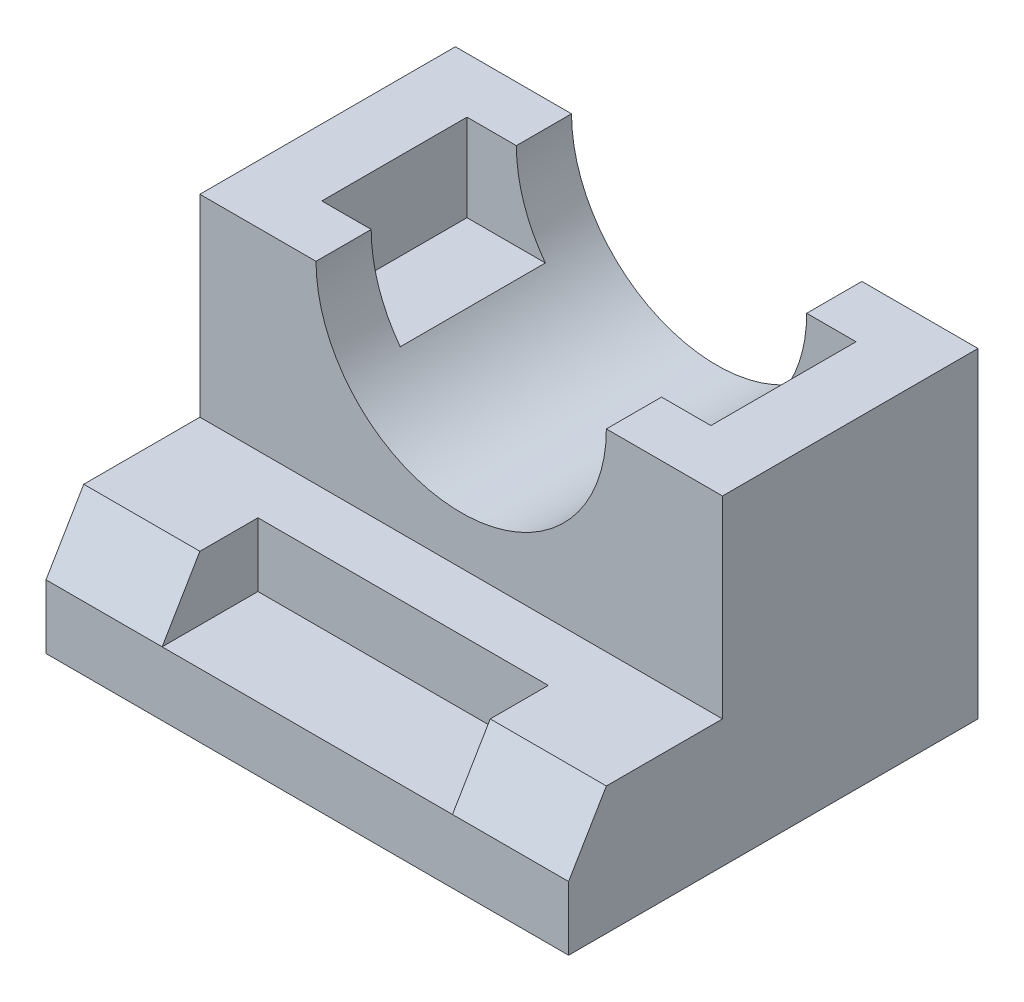
SolidWorks part; units mm, degrees
ref_plane "Front Plane" through (0, 0, 0) normal (0, 0, 1) x (1, 0, 0)
ref_plane "Top Plane" through (0, 0, 0) normal (0, 1, 0) x (1, 0, 0)
ref_plane "Right Plane" through (0, 0, 0) normal (1, 0, 0) x (0, 0, -1)
sketch "Sketch1" plane through (0, 0, 0) normal (1, 0, 0) x (0, 0, -1)
  line L0 (0, 0) -> (1117.6, 0)
  line L1 (1117.6, 0) -> (1117.6, 1403.35)
  line L2 (1117.6, 1403.35) -> (0, 1403.35)
  line L3 (0, 1403.35) -> (0, 0)
extrude "Boss-Extrude1" add sketch "Sketch1" along normal blind 2286 contours L3 L0 L1 L2
sketch "Sketch2" plane through (0, 0, 0) normal (0, 0, 1) x (1, 0, 0)
  line L0 (0, 0) -> (0, 558.8)
  line L1 (0, 1403.35) -> (0, 0) construction
  line L2 (0, 558.8) -> (2286, 558.8)
  line L3 (2286, 1403.35) -> (2286, 0) construction
  line L4 (2286, 558.8) -> (2286, 0)
  line L5 (2286, 0) -> (0, 0) construction
  line L6 (2286, 0) -> (0, 0)
  dimension "D1" = 2286
  dimension "D2" = 558.8
  dimension "D3" = 1403.35
extrude "Boss-Extrude2" add sketch "Sketch2" along normal blind 673.1 contours L6 L0 L2 L4
sketch "Sketch3" plane through (0, 0, 0) normal (-1, 0, 0) x (0, 0, 1)
  line L2 (673.1, 0) -> (673.1, 558.8) construction
  line L4 (673.1, 558.8) -> (0, 558.8) construction
  line L5 (508, 558.8) -> (673.1, 279.4)
  line L6 (508, 558.8) -> (673.1, 558.8)
  line L7 (673.1, 558.8) -> (673.1, 279.4)
  dimension "D1" = 324.5341
extrude "Cut-Extrude1" cut sketch "Sketch3" against normal blind 2286 contours L5 L7 L6
sketch "Sketch7" plane through (0, 0, 0) normal (0, 0, 1) x (1, 0, 0)
  line L0 (0, 1403.35) -> (0, 558.8) construction
  line L1 (2286, 279.4) -> (0, 279.4) construction
  line L2 (508, 279.4) -> (1778, 279.4)
  line L3 (1778, 279.4) -> (1778, 558.8)
  line L4 (0, 558.8) -> (2286, 558.8) construction
  line L5 (1778, 558.8) -> (508, 558.8)
  line L6 (508, 558.8) -> (508, 279.4)
  dimension "D1" = 508
  dimension "D2" = 1778
  dimension "D3" = 2286
extrude "Cut-Extrude2" cut sketch "Sketch7" along normal blind 673.1
sketch "Sketch8" plane through (0, 0, 0) normal (0, 0, 1) x (1, 0, 0)
  line L0 (508, 558.8) -> (1778, 558.8)
  line L1 (1778, 558.8) -> (2286, 558.8) construction
  line L2 (2286, 558.8) -> (1778, 558.8) construction
  line L3 (1778, 558.8) -> (1778, 279.4)
  line L4 (1778, 279.4) -> (508, 279.4)
  line L5 (508, 279.4) -> (508, 558.8)
extrude "Boss-Extrude3" add sketch "Sketch8" along normal blind 254 contours L5 L0 L3 L4
sketch "Sketch9" plane through (0, 0, 0) normal (0, 0, 1) x (1, 0, 0)
  line L0 (2286, 1403.35) -> (0, 1403.35) construction
  line L2 (508, 1403.35) -> (1778, 1403.35)
  arc A0 (508, 1403.35) -> (1778, 1403.35) centre (1143, 1403.35) ccw
  dimension "D1" = 635
extrude "Cut-Extrude3" cut sketch "Sketch9" against normal blind 1117.6 contours A0 L2
sketch "Sketch10" plane through (0, 1403.35, 0) normal (0, 1, 0) x (1, 0, 0)
  line L0 (1143, 1117.6) -> (1143, 0) construction
  line L2 (1778, 1117.6) -> (508, 1117.6) construction
  line L3 (292.1, 876.3) -> (292.1, 241.3)
  line L4 (292.1, 241.3) -> (673.1, 241.3)
  line L5 (673.1, 241.3) -> (673.1, 876.3)
  line L6 (673.1, 876.3) -> (292.1, 876.3)
  line L7 (508, 0) -> (1778, 0) construction
  line L8 (508, 1117.6) -> (508, 0) construction
  line L9 (1612.9, 876.3) -> (1993.9, 876.3)
  line L10 (1612.9, 241.3) -> (1612.9, 876.3)
  line L11 (1993.9, 241.3) -> (1612.9, 241.3)
  line L12 (1993.9, 876.3) -> (1993.9, 241.3)
  dimension "D1" = 165.1
  dimension "D2" = 215.9
  dimension "D3" = 241.3
  dimension "D4" = 876.3
extrude "Cut-Extrude4" cut sketch "Sketch10" against normal blind 381
